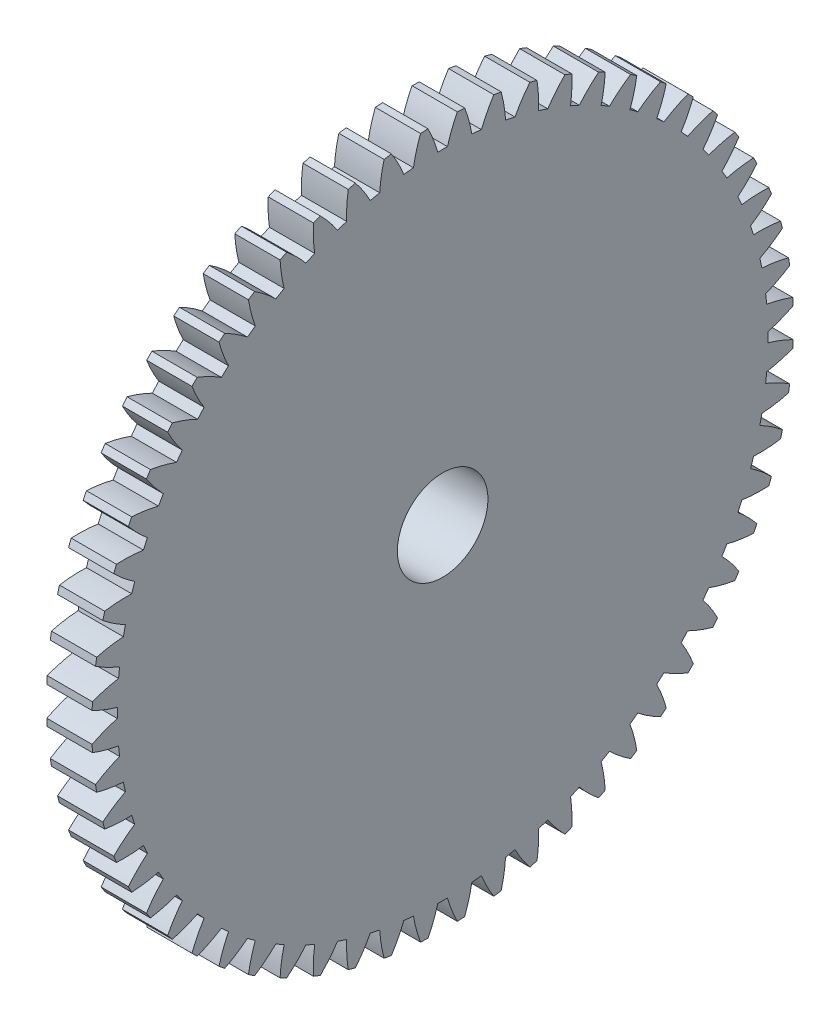
SolidWorks part; units mm, degrees
material "ABS"
ref_plane "Plane1" through (0, 0, 0) normal (0, 0, 1) x (1, 0, 0)
ref_plane "Plane2" through (0, 0, 0) normal (0, 1, 0) x (1, 0, 0)
ref_plane "Plane3" through (0, 0, 0) normal (1, 0, 0) x (0, 0, -1)
sketch "HoldingSke" plane through (0, 0, 0) normal (0, 1, 0) x (1, 0, 0)
  line L0 (0, 0) -> (203.2, -351.9527)
  line L1 (-15, 0) -> (100, 0) construction
  line L2 (0, 0) -> (-2.1039, 2.3779)
  line L3 (0, 0) -> (-11.863, 4.5341)
  line L4 (0, 0) -> (4.318, 7.479)
  line L5 (0, 0) -> (-23.7986, -8.8762)
  line L6 (0, 0) -> (-5.2639, -3.5516)
  line L7 (-2.1039, 2.3779) -> (3.3635, 27.1825)
  line L8 (-76.2, 54.61) -> (-61.976, 54.61)
  line L9 (-71.009, 38.7566) -> (-53.1078, 45.2721)
  line L10 (-76.2, 71.12) -> (104.1128, 71.12)
  line L11 (0, 0) -> (-6.35, 0)
  line L12 (-76.2, 101.6) -> (-76.1428, 101.6)
  line L13 (24.9733, 27.94) -> (52.9518, 28.4284)
  line L14 (24.9733, 27.94) -> (24.9746, 27.94)
  line L15 (24.9733, 27.94) -> (100.4006, 29.5858)
  circle A0 centre (0, 0) radius 6.35
  circle A1 centre (0, 0) radius 15.875
  circle A2 centre (0, 0) radius 15.875
  circle A3 centre (0, 0) radius 6.35
  dimension "MHD" = 31.75
  dimension "Hub_dia" = 31.75
  dimension "Bore" = 12.7
  dimension "MBD" = 12.7
  dimension "Num_teeth" = 60
  dimension "Pitch_radius" = 180.3128
  dimension "Pitch" = 406.4
  dimension "Width" = 6.35
  dimension "Overall_len" = 25.4
  dimension "Show_teeth" = 60
  dimension "Thickness" = 6.35
  dimension "OAL" = 25.4001
  dimension "T_dim" = 14.224
  dimension "Ap" = 20
  dimension "H" = 19.05
  dimension "Backlash" = 0.0571
  dimension "Addendum_fac" = 1
  dimension "Dedendum_fac" = 1.25
  dimension "Clearance_fac" = 0.25
  dimension "Dedendum_add" = 0.0013
sketch "BasProSke" plane through (0, 0, 0) normal (0, 1, 0) x (1, 0, 0)
  line L0 (-10, 0) -> (60, 0) construction
  line L1 (0, 0) -> (0, 49.2125)
  line L2 (0, 0) -> (6.35, 0)
  line L3 (6.35, 0) -> (6.35, 49.2125)
  line L4 (6.35, 49.2125) -> (0, 49.2125)
  dimension "Diameter" = 98.425
  dimension "Thickness" = 6.35
revolve "Base-Revolve" add sketch "BasProSke" angle 360 about L0
sketch "TooCutSke" plane through (0, 0, 0) normal (1, 0, 0) x (0, 0, -1)
  line L1 (0, 0) -> (0, 107) construction
  line L2 (0, 0) -> (-1.3467, 47.606) construction
  line L3 (0, 0) -> (-4.9836, 95.0919) construction
  line L4 (-1.3467, 47.606) -> (-2.4918, 47.5459) construction
  arc A0 (0.6776, 45.6343) -> (-0.6776, 45.6343) centre (0, 0) ccw
  arc A1 (2.0706, 49.1943) -> (-2.0706, 49.1943) centre (0, 0) ccw
  circle A2 centre (0, 0) radius 47.625 construction
  circle A3 centre (0, 0) radius 44.7529 construction
  arc A4 (-0.6776, 45.6343) -> (-2.0706, 49.1943) centre (-19.0248, 40.5077) ccw
  arc A5 (2.0706, 49.1943) -> (0.6776, 45.6343) centre (19.0248, 40.5077) ccw
  dimension "Root_dia" = 91.2787
  dimension "Overcut_dia" = 98.4758
  dimension "Pitch_dia" = 95.25
  dimension "Base_dia" = 89.5057
  dimension "Flank_rad" = 19.05
  dimension "Half_ang" = 3
  dimension "Half_CT" = 1.1467
extrude "ToothCut" cut sketch "TooCutSke" along normal through all
fillet "Breaks" [suppressed] radius 0.0318
fillet "RootFillets" [suppressed] radius 0.3981
pattern_circular "TeethCuts" count 60 every 6 about axis through (-10, 0, 0) along (1, 0, 0) of "ToothCut", "RootFillets", "Breaks"
sketch "HubNeaOneSke" plane through (0, 0, 0) normal (-1, 0, 0) x (0, 0, 1)
  circle A0 centre (0, 0) radius 15.875
  dimension "Diameter" = 31.75
extrude "HubNearOne" add sketch "HubNeaOneSke" along normal blind 19.0501
sketch "HubNeaBotSke" plane through (0, 0, 0) normal (-1, 0, 0) x (0, 0, 1)
  circle A0 centre (0, 0) radius 15.875
  dimension "Diameter" = 31.75
extrude "HubNearBoth" [suppressed] add sketch "HubNeaBotSke" along normal blind 9.525
ref_plane "FarPln" through (6.35, 0, 0) normal (1, 0, 0) x (0, 0, -1)
sketch "HubFarSke" plane through (6.35, 0, 0) normal (1, 0, 0) x (0, 0, -1)
  circle A0 centre (0, 0) radius 15.875
  dimension "Diameter" = 31.75
extrude "HubFar" [suppressed] add sketch "HubFarSke" along normal blind 9.525
sketch "BorSke" plane through (0, 0, 0) normal (1, 0, 0) x (0, 0, -1)
  circle A0 centre (0, 0) radius 6.35
  dimension "Diameter" = 12.7
extrude "Bore" cut sketch "BorSke" along normal mid plane 50.8001
sketch "KeySke" plane through (0, 0, 0) normal (1, 0, 0) x (0, 0, -1)
  line L0 (-1.5875, 0) -> (-1.5875, 7.874)
  line L1 (-1.5875, 7.874) -> (1.5875, 7.874)
  line L2 (1.5875, 7.874) -> (1.5875, 0)
  line L3 (0, 0) -> (0, 34) construction
  line L4 (-1.5875, 0) -> (1.5875, 0)
  dimension "Offset" = 7.874
  dimension "Width" = 3.175
extrude "Keyway" [suppressed] cut sketch "KeySke" along normal mid plane 50.8001
pattern_circular "Keyway2" [suppressed] count 2 every 90 about axis through (-10, 0, 0) along (1, 0, 0)
sketch "Sketch1" plane through (0, 0, 0) normal (0, 0, 1) x (1, 0, 0)
  line L0 (0, 0) -> (-19.0501, 0) construction
  line L1 (0, 15.875) -> (0, -15.875) construction
  line L2 (-19.0501, 15.875) -> (-19.0501, -15.875) construction
  circle A0 centre (-9.525, 0) radius 1.5875
  dimension "D1" = 3.175
extrude "Cut-Extrude1" cut sketch "Sketch1" against normal through all and the other way through all
fillet "Fillet1" radius 1.27 3 edges at (-19.0501, 0, 6.35) (-19.0501, 0, 15.875) (0, 0, -15.875)
equation "' \"Pitch@HoldingSke\" = 4"
equation "' \"Num_teeth@HoldingSke\" = 12"
equation "' \"Ap@HoldingSke\" =  20"
equation "' \"Width@HoldingSke\" = 0.5"
equation "' \"Hub_dia@HoldingSke\"= 1"
equation "' \"Overall_len@HoldingSke\" = 1.0"
equation "' \"Bore@HoldingSke\" = 0.75"
equation "' \"T_dim@HoldingSke\" = 0.85"
equation "' \"Width@KeySke\" = 0.25"
equation "' \"Show_teeth@HoldingSke\" = 13"
equation "' \"Backlash@HoldingSke\" = 0.009"
equation "' \"Addendum_fac@HoldingSke\" = 1.0"
equation "' \"Dedendum_fac@HoldingSke\" = 1.25"
equation "' \"Dedendum_add@HoldingSke\" = 0.00005"
equation "' \"Clearance_fac@HoldingSke\" = 0.25"
equation "' \"Pitch@HoldingSke\" = 0.5"
equation "' \"Num_teeth@HoldingSke\" = 23"
equation "' \"Show_teeth@HoldingSke\" = 23"
equation "' \"Backlash@HoldingSke\" = 0.0375"
equation "\"Overcut_dia@TooCutSke\" = (\"Num_teeth@HoldingSke\" + 2 * \"Addendum_fac@HoldingSke\") / \"Pitch@HoldingSke\" + 0.002"
equation "\"Pitch_dia@TooCutSke\" = \"Num_teeth@HoldingSke\" / \"Pitch@HoldingSke\""
equation "\"Base_dia@TooCutSke\" = \"Num_teeth@HoldingSke\" / \"Pitch@HoldingSke\" * cos((\"Ap@HoldingSke\"  * 3.14159265 / 180))"
equation "\"Root_dia@TooCutSke\" = (\"Num_teeth@HoldingSke\" + 2) / \"Pitch@HoldingSke\" - 2 * (\"Addendum_fac@HoldingSke\" + \"Dedendum_fac@HoldingSke\") / \"Pitch@HoldingSke\" - \"Dedendum_add@HoldingSke\" * 2"
equation "\"Half_ang@TooCutSke\" = 180 / \"Num_teeth@HoldingSke\""
equation "\"Half_CT@TooCutSke\" = \"Num_teeth@HoldingSke\" / \"Pitch@HoldingSke\" * sin((3.14159265 / 2 / \"Num_teeth@HoldingSke\")) / 2 - 7 * \"Backlash@HoldingSke\" / 4"
equation "\"Flank_rad@TooCutSke\" = \"Num_teeth@HoldingSke\" / \"Pitch@HoldingSke\" / 5"
equation "\"Radius@RootFillets\" = \"Clearance_fac@HoldingSke\" / \"Pitch@HoldingSke\" + \"Dedendum_add@HoldingSke\""
equation "\"Break_rad@Breaks\" = 0.02 / \"Pitch@HoldingSke\""
equation "\"Thickness@HoldingSke\" = \"Width@HoldingSke\""
equation "\"OAL@HoldingSke\" = \"Thickness@HoldingSke\""
equation "\"MHD@HoldingSke\" = (\"Num_teeth@HoldingSke\" + 2) / \"Pitch@HoldingSke\" - 2 * (\"Addendum_fac@HoldingSke\" + \"Dedendum_fac@HoldingSke\")  / \"Pitch@HoldingSke\" - \"Dedendum_add@HoldingSke\" * 2"
equation "\"MBD@HoldingSke\" = (\"Num_teeth@HoldingSke\" + 2) / \"Pitch@HoldingSke\" - 2 * (\"Addendum_fac@HoldingSke\" + \"Dedendum_fac@HoldingSke\")  / \"Pitch@HoldingSke\" - \"Dedendum_add@HoldingSke\" * 2 - 0.002"
equation "\"MHD@HoldingSke\" = ((sgn( \"MHD@HoldingSke\" - \"Hub_dia@HoldingSke\" )-1)*( \"MHD@HoldingSke\" - \"Hub_dia@HoldingSke\" ))/-2+ \"Hub_dia@HoldingSke\""
equation "\"MBD@HoldingSke\" = ((sgn( \"MBD@HoldingSke\" - \"Bore@HoldingSke\" )-1)*( \"MBD@HoldingSke\" - \"Bore@HoldingSke\" ))/-2+ \"Bore@HoldingSke\""
equation "\"OAL@HoldingSke\" = ((sgn( \"OAL@HoldingSke\" - \"Overall_len@HoldingSke\" )+1)*( \"OAL@HoldingSke\" - \"Overall_len@HoldingSke\" ))/2 + \"Overall_len@HoldingSke\" + 0.000002"
equation "\"Num_teeth@TeethCuts\" = int( \"Show_teeth@HoldingSke\" ) + 1"
equation "\"Num_teeth@TeethCuts\" = ((sgn( \"Num_teeth@TeethCuts\" - \"Num_teeth@HoldingSke\" )-1)*( \"Num_teeth@TeethCuts\" - \"Num_teeth@HoldingSke\" ))/-2+ \"Num_teeth@HoldingSke\""
equation "\"Num_teeth@TeethCuts\" = ((sgn( \"Num_teeth@TeethCuts\" - 2.0)+1)*( \"Num_teeth@TeethCuts\" - 2.0))/2 +2.0"
equation "\"Angle@TeethCuts\" = 360.0 / \"Num_teeth@HoldingSke\""
equation "\"Diameter@BasProSke\" = (\"Num_teeth@HoldingSke\" + 2 * \"Addendum_fac@HoldingSke\") / \"Pitch@HoldingSke\""
equation "\"Thickness@BasProSke\"  = \"Thickness@HoldingSke\""
equation "' \"Fillet_rad@BasProSke\" =  \"Thickness@HoldingSke\" * 0.05"
equation "\"MHD@HoldingSke\" = ((sgn( \"MHD@HoldingSke\" - \"Root_dia@TooCutSke\" )-1)*( \"MHD@HoldingSke\" - \"Root_dia@TooCutSke\" ))/-2+ \"Root_dia@TooCutSke\""
equation "\"Diameter@HubNeaOneSke\" = \"MHD@HoldingSke\""
equation "\"Length@HubNearOne\" = \"OAL@HoldingSke\" - \"Thickness@BasProSke\""
equation "\"Diameter@HubNeaBotSke\" = \"MHD@HoldingSke\""
equation "\"Length@HubNearBoth\" = ( \"OAL@HoldingSke\" - \"Thickness@BasProSke\" ) / 2.0"
equation "\"Thickness@FarPln\" = \"Thickness@BasProSke\""
equation "\"Diameter@HubFarSke\" = \"MHD@HoldingSke\""
equation "\"Length@HubFar\" = ( \"OAL@HoldingSke\" - \"Thickness@BasProSke\" ) / 2.0"
equation "\"Diameter@BorSke\" = \"MBD@HoldingSke\""
equation "\"D1@Bore\" = \"OAL@HoldingSke\" * 2.0"
equation "\"D1@Keyway\" = \"OAL@HoldingSke\" * 2.0"
equation "\"Offset@KeySke\" = \"T_dim@HoldingSke\" - \"MBD@HoldingSke\" / 2.0"
